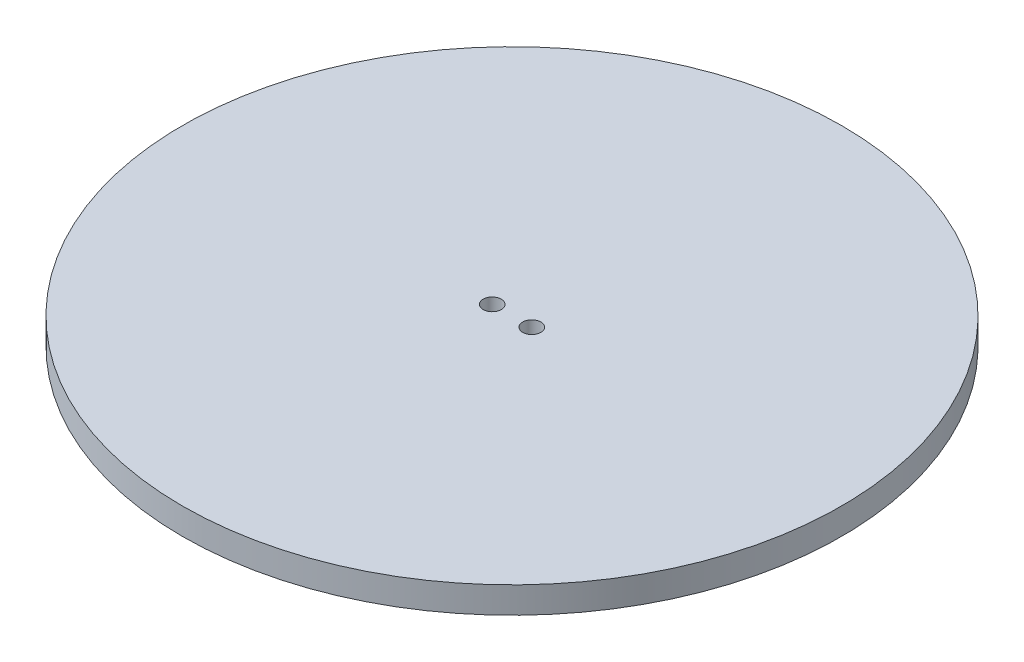
SolidWorks part; units mm, degrees
ref_plane "Front Plane" through (0, 0, 0) normal (0, 0, 1) x (1, 0, 0)
ref_plane "Top Plane" through (0, 0, 0) normal (0, 1, 0) x (1, 0, 0)
ref_plane "Right Plane" through (0, 0, 0) normal (1, 0, 0) x (0, 0, -1)
sketch "Sketch1" plane through (0, 0, 0) normal (0, 1, 0) x (1, 0, 0)
  circle A0 centre (0, 0) radius 100
  dimension "D1" = 200
extrude "Boss-Extrude1" add sketch "Sketch1" along normal blind 8
sketch "Sketch2" plane through (0, 8, 0) normal (0, 1, 0) x (1, 0, 0)
  circle A0 centre (6, 0) radius 2.75
  circle A1 centre (-6, 0) radius 2.75
  dimension "D1" = 6
  dimension "D2" = 6
  dimension "D3" = 5.5
  dimension "D4" = 5.5
extrude "Cut-Extrude1" cut sketch "Sketch2" against normal blind 8
